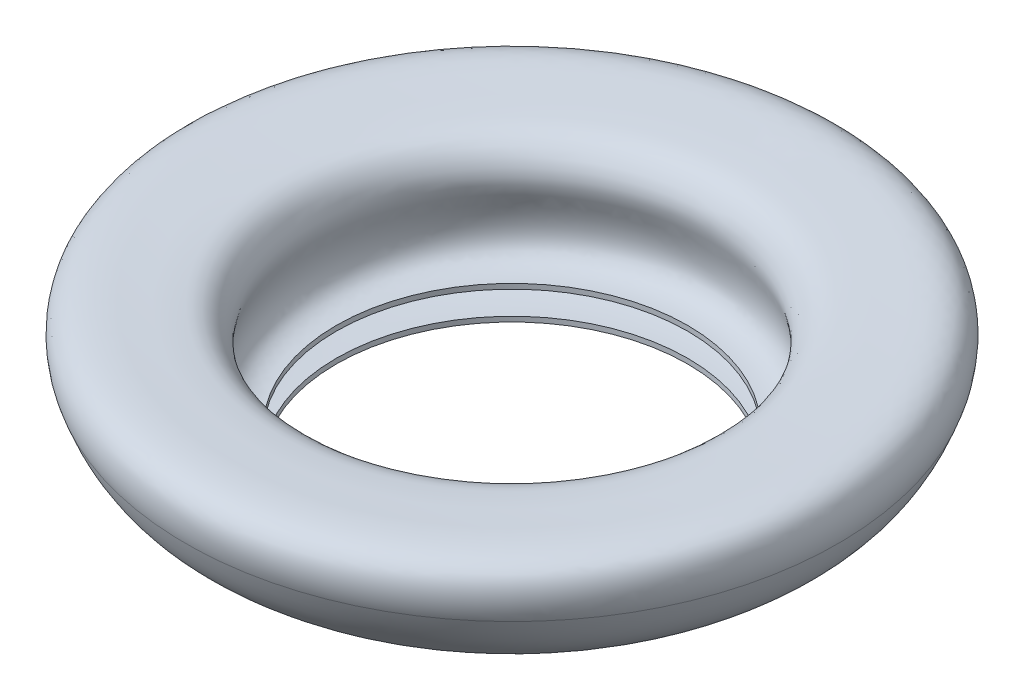
SolidWorks part; units mm, degrees
material "ABS PC"
ref_plane "Front Plane" through (0, 0, 0) normal (0, 0, 1) x (1, 0, 0)
ref_plane "Top Plane" through (0, 0, 0) normal (0, 1, 0) x (1, 0, 0)
ref_plane "Right Plane" through (0, 0, 0) normal (1, 0, 0) x (0, 0, -1)
sketch "Sketch1" plane through (0, 0, 0) normal (0, 0, 1) x (1, 0, 0)
  line L0 (-42, 9) -> (42, 9) construction
  line L1 (-20, 9) -> (20, 9) construction
  line L2 (-20, 9) -> (-20, -9) construction
  line L3 (-20, -9) -> (20, -9) construction
  line L4 (20, 9) -> (20, -9) construction
  line L5 (-20, 9) -> (20, -9) construction
  line L6 (-20, -9) -> (20, 9) construction
  line L7 (-21, -4.5) -> (-21, -5.1)
  line L8 (-21, -8.5) -> (-21, -7.9)
  line L9 (0, -24.0899) -> (0, 24.0899) construction
  line L10 (-32.8, 7.2949) -> (32.8, 7.2949) construction
  line L11 (-26.15, 0.5949) -> (26.15, 0.5949) construction
  line L12 (-32.8, 7.2949) -> (-32.8, 0.5949) construction
  line L13 (-32.8, 7.2949) -> (-32.8, 0.5949) construction
  line L14 (-32.8, 7.2949) -> (-26.15, 7.2949) construction
  line L15 (-32.8, 0.5949) -> (-26.15, 0.5949) construction
  line L16 (-26.15, 7.2949) -> (-26.15, 0.5949) construction
  spline S0 degree 3 poles (-21, -8.5) (-24.2991, -8.5) (-29.5857, -6.4267) (-36.5329, -2.8623) (-38.4174, 1.3863) (-38.9787, 2.9095) knots 0 0 0 0 0.4246 0.77038 1 1 1 1
  spline S1 degree 3 poles (-21, -4.5) (-25.1667, -4.5) (-24.9999, -0.0229) (-23.0397, 4.4847) (-25.3481, 8.5237) (-31.2066, 8.1046) (-39.2077, 9.7222) (-39.6125, 4.6296) (-38.9787, 2.9095) knots 0 0 0 0 0.242243 0.340662 0.444266 0.598217 0.862644 1 1 1 1
  spline S2 degree 1 poles (-21, -5.1) (-38.4157, 3.117) knots 0 0 1 1 construction
  spline S3 degree 1 poles (-21, -7.9) (-38.4157, 3.117) knots 0 0 1 1 construction
  spline S4 degree 3 poles (-21, -5.1) (-21.2733, -5.1) (-21.8405, -5.0716) (-22.801, -4.9039) (-23.8129, -4.4866) (-24.6698, -3.6705) (-25.3057, -2.315) (-25.3494, -0.4294) (-24.7654, 1.8496) (-24.1927, 3.429) (-24.1478, 4.5125) (-24.3739, 5.3779) (-24.8272, 6.2158) (-25.6359, 7.1241) (-26.821, 7.6468) (-28.475, 7.7584) (-29.9938, 7.7886) (-31.6002, 7.8868) (-33.6046, 8.0678) (-35.8075, 8.1158) (-37.5101, 7.7414) (-38.4631, 6.9358) (-38.8347, 5.5404) (-38.7388, 4.1944) (-38.5425, 3.4611) (-38.4157, 3.117) knots 0 0 0 0 0.015625 0.03125 0.0625 0.09375 0.125 0.1875 0.25 0.3125 0.34375 0.375 0.40625 0.4375 0.5 0.5625 0.59375 0.625 0.6875 0.75 0.8125 0.875 0.9375 0.96875 1 1 1 1
  spline S5 degree 3 poles (-38.4157, 3.117) (-38.2616, 2.6989) (-37.9411, 1.8793) (-37.3546, 0.6192) (-36.6627, -0.5721) (-35.5858, -1.9795) (-33.8868, -3.4027) (-31.4606, -4.7583) (-28.8704, -5.9477) (-26.3238, -6.9885) (-24.1595, -7.59) (-22.3831, -7.8526) (-21.4586, -7.9) (-21, -7.9) knots 0 0 0 0 0.0625 0.125 0.1875 0.25 0.375 0.5 0.625 0.75 0.875 0.9375 1 1 1 1
  point P0 (0, 0)
  point P5 (0, 0)
  point P20 (0, 9)
  point P28 (0, 7.2949)
  point P31 (0, 0)
  point P34 (0, 0.5949)
  dimension "D1" = 40
  dimension "D2" = 18
  dimension "D3" = 0.5
  dimension "D4" = 4
  dimension "D5" = 1
  dimension "D7" = 22
  dimension "D9" = 65.6
  dimension "D10" = 52.3
  dimension "D11" = 6.7
  dimension "D8" = 0.6
revolve "Revolve1" add sketch "Sketch1" angle 360 about L9
